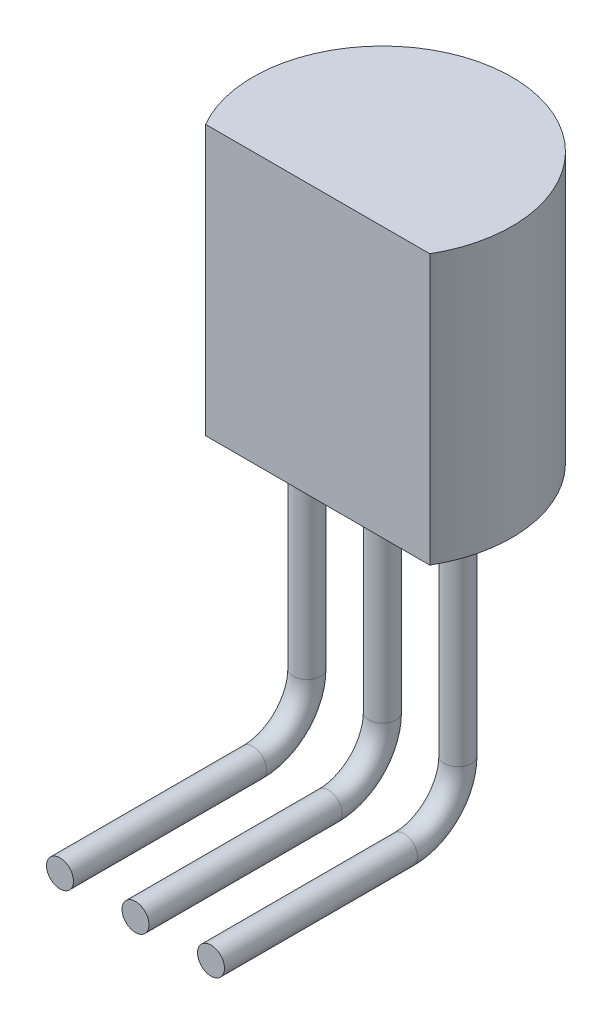
SolidWorks part; units mm, degrees
ref_plane "Plan de face" through (0, 0, 0) normal (0, 0, 1) x (1, 0, 0)
ref_plane "Plan de dessus" through (0, 0, 0) normal (0, 1, 0) x (1, 0, 0)
ref_plane "Plan de droite" through (0, 0, 0) normal (1, 0, 0) x (0, 0, -1)
sketch "Esquisse2" plane through (0, 0, 0) normal (0, 1, 0) x (1, 0, 0)
  line L0 (-2.0785, -1.2) -> (2.0785, -1.2)
  arc A0 (2.0785, -1.2) -> (-2.0785, -1.2) centre (0, 0) ccw
  dimension "D1" = 4.8
  dimension "D2" = 1.2
extrude "Extrusion1" add sketch "Esquisse2" along normal blind 5
sketch "Esquisse6" plane through (0, 0, 0) normal (0, -1, 0) x (1, 0, 0)
  line L0 (0, 3.1204) -> (0, -4.1965) construction
  line L1 (1.4, -4.1965) -> (1.4, 3.1204) construction
  line L2 (-1.4, -4.1965) -> (-1.4, 3.1204) construction
  line L3 (3.6641, 0) -> (-4.9473, 0) construction
  circle A0 centre (0, 0) radius 0.25
  circle A2 centre (1.4, 0) radius 0.25
  circle A3 centre (-1.4, 0) radius 0.25
  dimension "D1" = 1.4
  dimension "D2" = 1.4
sketch "Esquisse8" plane through (0, 0, 0) normal (1, 0, 0) x (0, 0, -1)
  line L1 (-3.261, -5) -> (6.2315, -5) construction
  line L4 (0, 0) -> (0, -4)
  line L6 (-1, -5) -> (-4.5781, -5)
  arc A1 (0, -4) -> (-1, -5) centre (-1, -4) cw
sweep "Balayage1" add profiles "Esquisse6" path "Esquisse8"
